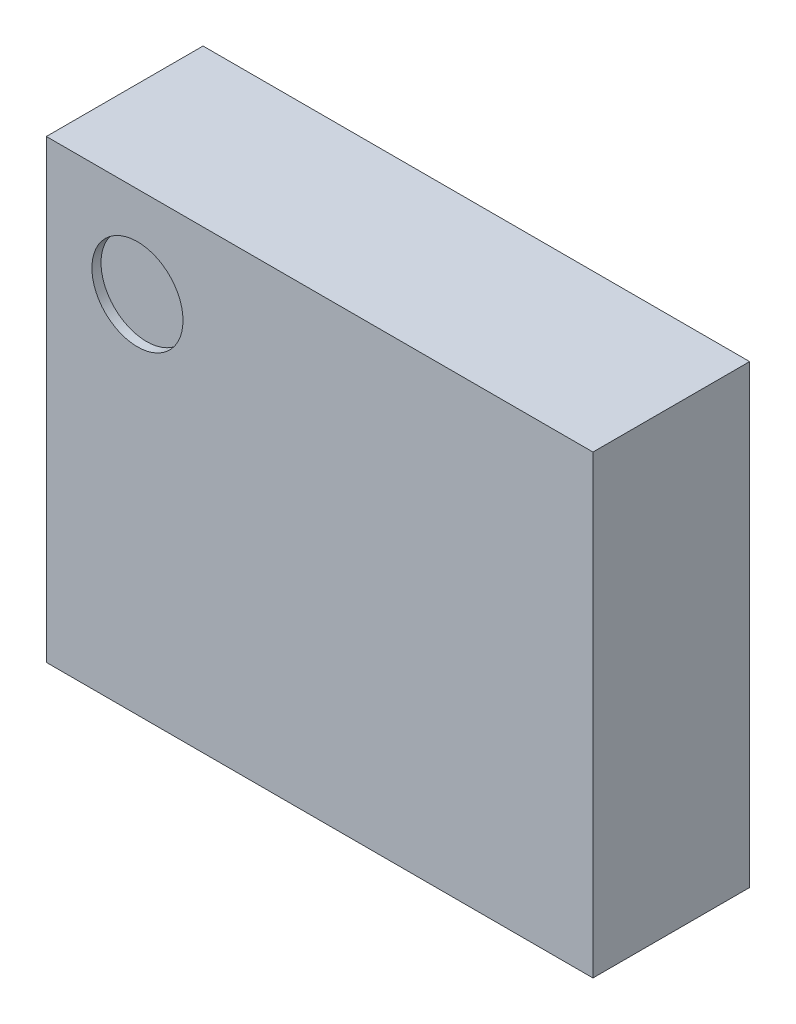
SolidWorks part; units mm, degrees
ref_plane "Front Plane" through (0, 0, 0) normal (0, 0, 1) x (1, 0, 0)
ref_plane "Top Plane" through (0, 0, 0) normal (0, 1, 0) x (1, 0, 0)
ref_plane "Right Plane" through (0, 0, 0) normal (1, 0, 0) x (0, 0, -1)
sketch "Sketch1" plane through (0, 0, 0) normal (0, 0, 1) x (1, 0, 0)
  line L1 (-1.5, 1.25) -> (1.5, 1.25)
  line L2 (-1.5, 1.25) -> (-1.5, -1.25)
  line L3 (-1.5, -1.25) -> (1.5, -1.25)
  line L4 (1.5, 1.25) -> (1.5, -1.25)
  line L5 (-1.5, 1.25) -> (1.5, -1.25) construction
  line L6 (-1.5, -1.25) -> (1.5, 1.25) construction
  point P0 (0, 0)
  dimension "D1" = 3
  dimension "D2" = 2.5
extrude "Boss-Extrude1" add sketch "Sketch1" along normal blind 0.86
sketch "Sketch2" plane through (0, 0, 0.86) normal (0, 0, 1) x (1, 0, 0)
  line L0 (1.5, 1.25) -> (-1.5, 1.25) construction
  line L1 (-1.5, 1.25) -> (-1.5, -1.25) construction
  circle A0 centre (-1, 0.75) radius 0.25
  dimension "D1" = 0.5
  dimension "D2" = 0.5
  dimension "D3" = 0.5
extrude "Cut-Extrude1" cut sketch "Sketch2" against normal blind 0.05
